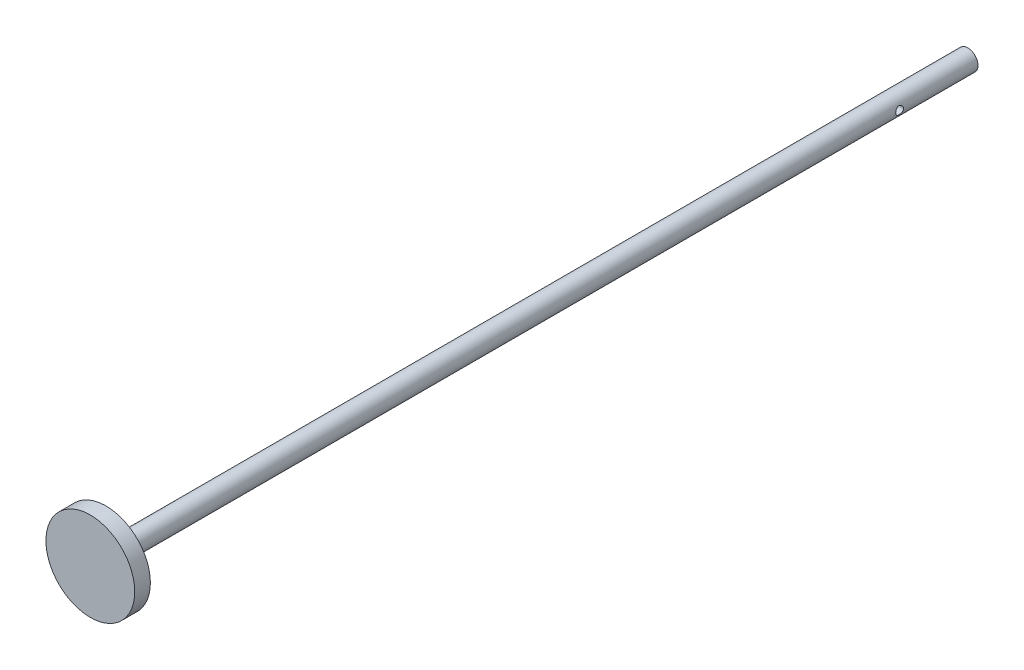
SolidWorks part; units mm, degrees
ref_plane "Płaszczyzna przednia" through (0, 0, 0) normal (0, 0, 1) x (1, 0, 0)
ref_plane "Płaszczyzna górna" through (0, 0, 0) normal (0, 1, 0) x (1, 0, 0)
ref_plane "Płaszczyzna prawa" through (0, 0, 0) normal (1, 0, 0) x (0, 0, -1)
sketch "Szkic1" plane through (0, 0, 0) normal (0, 0, 1) x (1, 0, 0)
  circle A0 centre (0, 0) radius 1.95
  dimension "D1" = 3.9
extrude "Dodanie-wyciągnięcie1" add sketch "Szkic1" along normal blind 165
sketch "Szkic2" plane through (0, 0, 165) normal (0, 0, 1) x (1, 0, 0)
  circle A0 centre (0, 0) radius 8.5
  dimension "D1" = 17
extrude "Dodanie-wyciągnięcie2" add sketch "Szkic2" along normal blind 3
ref_plane "Płaszczyzna1" through (-1.95, 0, 0) normal (-1, 0, 0) x (0, 0, 1)
sketch "Szkic6" plane through (-1.95, 0, 0) normal (-1, 0, 0) x (0, 0, 1)
  line L0 (0, 1.95) -> (0, -1.95) construction
  circle A0 centre (15, 0) radius 0.75
  dimension "D1" = 15
extrude "Wytnij-wyciągnięcie2" cut sketch "Szkic6" against normal blind 11
